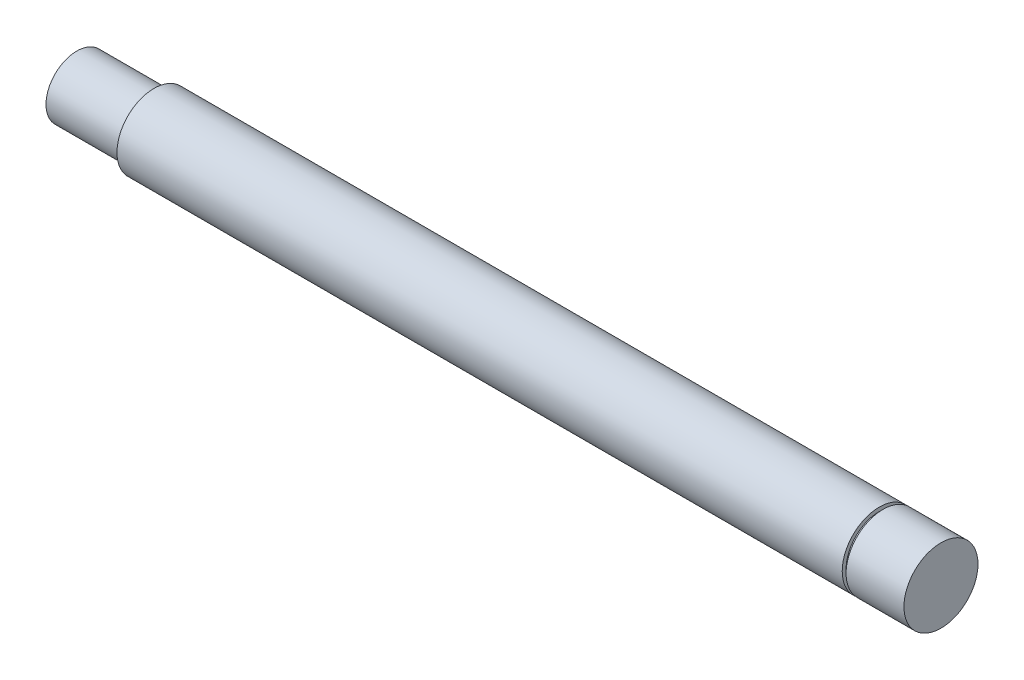
SolidWorks part; units mm, degrees
material "PW20:29:Sc:0:"
ref_plane "Front" through (0, 0, 0) normal (0, 0, 1) x (1, 0, 0)
ref_plane "Top" through (0, 0, 0) normal (0, 1, 0) x (1, 0, 0)
ref_plane "Right" through (0, 0, 0) normal (1, 0, 0) x (0, 0, -1)
sketch "Sketch1" plane through (0, 0, 0) normal (1, 0, 0) x (0, 0, -1)
  circle A0 centre (0, 0) radius 7.62
  dimension "D1" = 15.24
extrude "Base-Extrude" add sketch "Sketch1" along normal blind 177.8
ref_plane "Plane4" through (165.8937, 0, 0) normal (1, 0, 0) x (0, 0, -1)
sketch "Sketch2" plane through (165.8937, 0, 0) normal (1, 0, 0) x (0, 0, -1)
  circle A1 centre (0, 0) radius 6.8262
  circle A2 centre (0, 0) radius 6.8262
  circle A3 centre (0, 0) radius 7.62
  circle A4 centre (0, 0) radius 7.62
  dimension "D1" = 0.7937
  dimension "D2" = 0
extrude "Cut-Extrude1" cut sketch "Sketch2" against normal blind 0.7937
sketch "Sketch3" plane through (0, 0, 0) normal (-1, 0, 0) x (0, 0, 1)
  circle A0 centre (0, 0) radius 7.62 construction
  circle A1 centre (0, 0) radius 6.35
  circle A2 centre (0, 0) radius 6.35
  circle A3 centre (0, 0) radius 7.62
  dimension "D1" = 1.27
extrude "Cut-Extrude2" cut sketch "Sketch3" against normal blind 15.875
